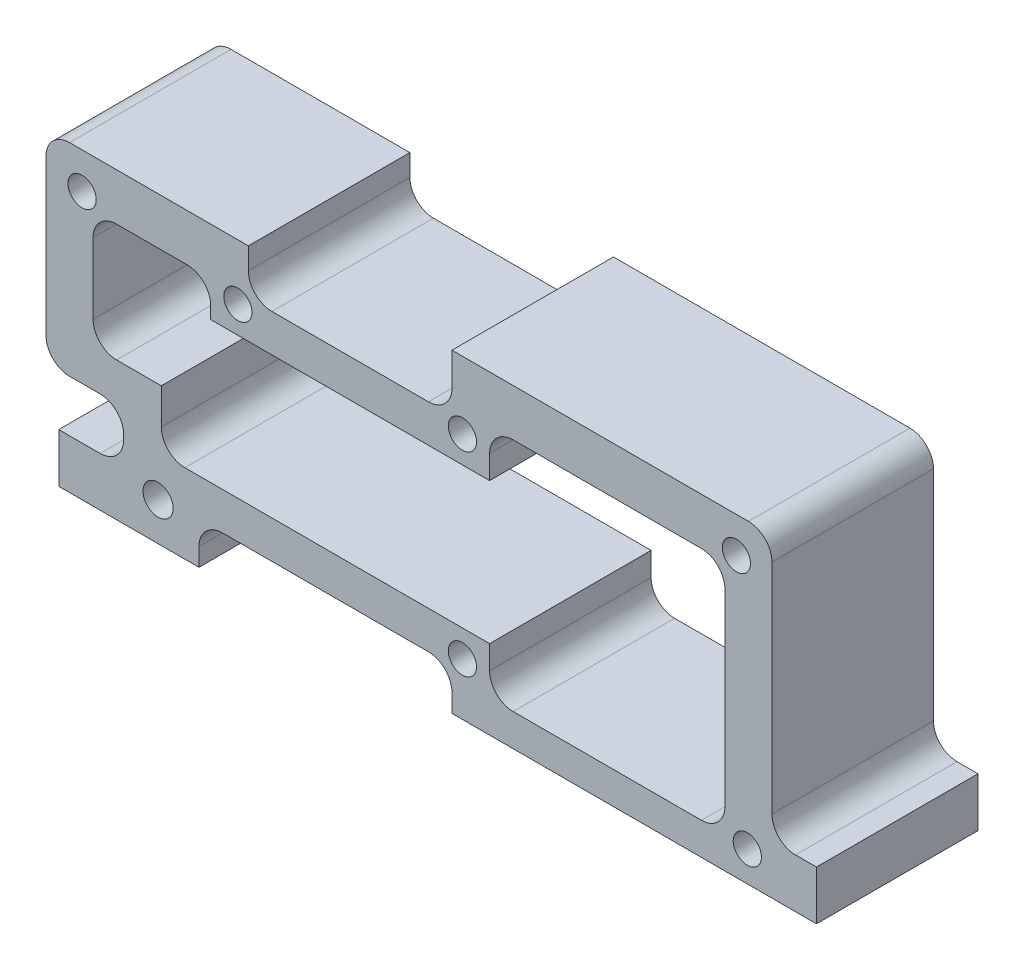
SolidWorks part; units mm, degrees
ref_plane "Front Plane" through (0, 0, 0) normal (0, 0, 1) x (1, 0, 0)
ref_plane "Top Plane" through (0, 0, 0) normal (0, 1, 0) x (1, 0, 0)
ref_plane "Right Plane" through (0, 0, 0) normal (1, 0, 0) x (0, 0, -1)
sketch "Sketch4" plane through (0, 0, 0) normal (0, 0, 1) x (1, 0, 0)
  line L0 (-42.3435, -2.9906) -> (-42.3435, 17.9644)
  line L1 (-40.6186, -19.7615) -> (-21.7055, -19.7615)
  line L2 (12.4321, -17.3234) -> (12.4321, -19.7615)
  line L3 (-15.0385, 21.1394) -> (-39.1685, 21.1394)
  line L4 (55.6121, -9.9457) -> (55.6121, 19.5066)
  line L5 (61.6185, -19.7615) -> (61.6185, -13.1207)
  line L6 (61.6185, -13.1207) -> (58.7871, -13.1207)
  line L7 (-40.6186, -19.7615) -> (-40.6186, -13.1207)
  line L8 (-40.6186, -13.1207) -> (-35.0405, -13.1207)
  line L9 (-18.5305, -14.1484) -> (9.2571, -14.1484)
  line L10 (12.4321, 18.2366) -> (12.4321, 22.6816)
  line L11 (-21.7055, -17.3234) -> (-21.7055, -19.7615)
  line L12 (12.4321, -19.7615) -> (61.6185, -19.7615)
  line L13 (9.2571, 15.0616) -> (-11.8635, 15.0616)
  line L14 (-15.0385, 18.2366) -> (-15.0385, 21.1394)
  line L15 (52.4371, 22.6816) -> (12.4321, 22.6816)
  line L16 (-39.1685, -6.1656) -> (-35.0405, -6.1656)
  line L17 (-31.8655, -9.3406) -> (-31.8655, -9.9457)
  line L53 (49.2621, -12.2434) -> (49.2621, 13.1566)
  line L54 (46.0871, 16.3316) -> (20.6871, 16.3316)
  line L55 (17.5121, 13.1566) -> (17.5121, 9.9816)
  line L56 (17.5121, 9.9816) -> (-20.1185, 9.9816)
  line L57 (-20.1185, 9.9816) -> (-20.1185, 11.6144)
  line L58 (-23.2935, 14.7894) -> (-32.8185, 14.7894)
  line L59 (-35.9935, 11.6144) -> (-35.9935, 2.0894)
  line L60 (-32.8185, -1.0856) -> (-26.7855, -1.0856)
  line L61 (-26.7855, -1.0856) -> (-26.7855, -5.8934)
  line L62 (-23.6105, -9.0684) -> (17.5121, -9.0684)
  line L63 (17.5121, -9.0684) -> (17.5121, -12.2434)
  line L64 (20.6871, -15.4184) -> (46.0871, -15.4184)
  arc A0 (-39.1685, 21.1394) -> (-42.3435, 17.9644) centre (-39.1685, 17.9644) ccw
  arc A1 (-42.3435, -2.9906) -> (-39.1685, -6.1656) centre (-39.1685, -2.9906) ccw
  arc A2 (-31.8655, -9.3406) -> (-35.0405, -6.1656) centre (-35.0405, -9.3406) ccw
  arc A3 (-31.8655, -9.9457) -> (-35.0405, -13.1207) centre (-35.0405, -9.9457) cw
  arc A4 (-18.5305, -14.1484) -> (-21.7055, -17.3234) centre (-18.5305, -17.3234) ccw
  arc A5 (12.4321, -17.3234) -> (9.2571, -14.1484) centre (9.2571, -17.3234) ccw
  arc A6 (55.6121, -9.9457) -> (58.7871, -13.1207) centre (58.7871, -9.9457) ccw
  arc A7 (55.6121, 19.5066) -> (52.4371, 22.6816) centre (52.4371, 19.5066) ccw
  arc A8 (12.4321, 18.2366) -> (9.2571, 15.0616) centre (9.2571, 18.2366) cw
  arc A9 (-11.8635, 15.0616) -> (-15.0385, 18.2366) centre (-11.8635, 18.2366) cw
  circle A12 centre (-27.2212, -14.6226) radius 2.032
  circle A16 centre (52.2874, -15.6781) radius 1.905
  circle A20 centre (13.8463, -12.6838) radius 1.905
  circle A22 centre (13.8463, 13.5969) radius 1.905
  circle A24 centre (-37.4743, 16.2702) radius 1.905
  circle A26 centre (-16.4527, 13.5969) radius 1.905
  circle A28 centre (50.815, 17.8845) radius 1.905
  arc A35 (49.2621, 13.1566) -> (46.0871, 16.3316) centre (46.0871, 13.1566) ccw
  arc A36 (20.6871, 16.3316) -> (17.5121, 13.1566) centre (20.6871, 13.1566) ccw
  arc A37 (-20.1185, 11.6144) -> (-23.2935, 14.7894) centre (-23.2935, 11.6144) ccw
  arc A38 (-32.8185, 14.7894) -> (-35.9935, 11.6144) centre (-32.8185, 11.6144) ccw
  arc A39 (-35.9935, 2.0894) -> (-32.8185, -1.0856) centre (-32.8185, 2.0894) ccw
  arc A40 (-26.7855, -5.8934) -> (-23.6105, -9.0684) centre (-23.6105, -5.8934) ccw
  arc A41 (17.5121, -12.2434) -> (20.6871, -15.4184) centre (20.6871, -12.2434) ccw
  arc A42 (46.0871, -15.4184) -> (49.2621, -12.2434) centre (46.0871, -12.2434) ccw
extrude "Extrude3" add sketch "Sketch4" along normal mid plane 21.7932 separate body
